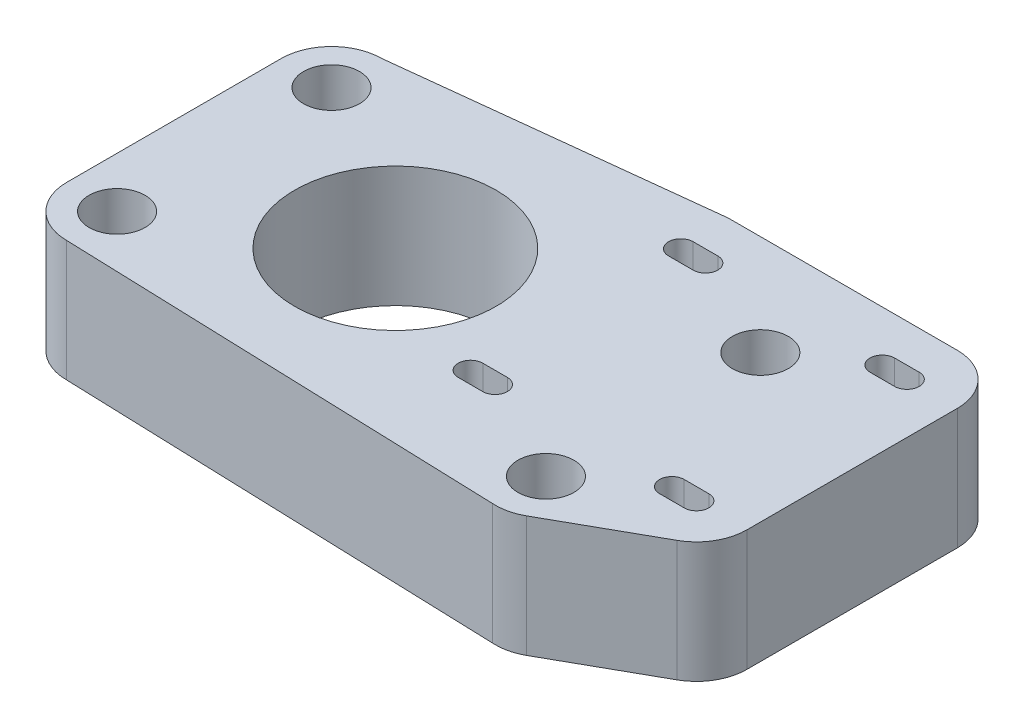
SolidWorks part; units mm, degrees
ref_plane "Front Plane" through (0, 0, 0) normal (0, 0, 1) x (1, 0, 0)
ref_plane "Top Plane" through (0, 0, 0) normal (0, 1, 0) x (1, 0, 0)
ref_plane "Right Plane" through (0, 0, 0) normal (1, 0, 0) x (0, 0, -1)
sketch "Sketch1" plane through (0, 0, 0) normal (0, 1, 0) x (1, 0, 0)
  line L0 (50.75, -48.725) -> (50.75, -55.125) construction
  line L1 (75.25, 55.125) -> (-75.25, 55.125)
  line L2 (75.25, 55.125) -> (75.25, -55.125)
  line L3 (75.25, -55.125) -> (-75.25, -55.125)
  line L4 (-75.25, 55.125) -> (-75.25, -55.125)
  line L5 (75.25, 55.125) -> (-75.25, -55.125) construction
  line L6 (75.25, -55.125) -> (-75.25, 55.125) construction
  line L7 (-48.4, -45.375) -> (-48.4, -55.125) construction
  line L8 (-48.4, -45.375) -> (-48.4, -42.875) construction
  line L9 (-48.4, -42.875) -> (-48.4, -40.375) construction
  line L10 (-48.4, -40.375) -> (-48.4, 2.525) construction
  line L12 (-50.9, -42.875) -> (-75.25, -42.875) construction
  line L13 (53.25, -46.225) -> (75.25, -46.225) construction
  line L14 (50.75, -43.725) -> (50.75, -0.825) construction
  circle A0 centre (-48.4, -42.875) radius 2.5
  circle A1 centre (50.75, -46.225) radius 2.5
  circle A2 centre (-48.4, 5.025) radius 2.5
  circle A3 centre (50.75, 1.675) radius 2.5
  point P0 (0, 0)
  dimension "D3" = 5
  dimension "D1" = 150.5
  dimension "D2" = 110.25
  dimension "D4" = 22
  dimension "D5" = 24.35
  dimension "D6" = 6.4
  dimension "D7" = 9.75
  dimension "D8" = 42.9
extrude "Boss-Extrude1" add sketch "Sketch1" along normal blind 27
sketch "Sketch2" plane through (0, 27, 0) normal (0, 1, 0) x (1, 0, 0)
  line L0 (22.0573, -34.1413) -> (24.5573, -34.1413) construction
  line L2 (22.0573, -29.6413) -> (22.0573, -38.6413) construction
  line L3 (27.0573, -34.1413) -> (24.5573, -34.1413) construction
  line L4 (27.0573, -38.6413) -> (27.0573, -29.6413) construction
  line L6 (67.0573, 12.8587) -> (69.5573, 12.8587) construction
  line L7 (67.0573, 17.3587) -> (67.0573, 8.3587) construction
  line L8 (69.5573, 12.8587) -> (72.0573, 12.8587) construction
  line L9 (72.0573, 8.3587) -> (72.0573, 17.3587) construction
  line L10 (24.5573, -34.1413) -> (69.5573, -34.1413) construction
  line L11 (69.5573, -34.1413) -> (69.5573, 12.8587) construction
  line L12 (69.5573, 12.8587) -> (24.5573, 12.8587) construction
  line L13 (24.5573, 12.8587) -> (24.5573, -34.1413) construction
  circle A3 centre (24.5573, -34.1413) radius 2.75
  circle A4 centre (69.5573, -34.1413) radius 2.75
  circle A5 centre (24.5573, 12.8587) radius 2.75
  circle A6 centre (69.5573, 12.8587) radius 2.75
  dimension "D1" = 5.5
sketch "Sketch3" plane through (0, 0, 0) normal (0, 1, 0) x (1, 0, 0)
  line L1 (-75.25, 55.125) -> (75.25, 55.125)
  line L2 (-75.25, 55.125) -> (-75.25, -55.125)
  line L3 (-75.25, -55.125) -> (75.25, -55.125)
  line L4 (75.25, 55.125) -> (75.25, -55.125)
  line L5 (150, 100) -> (-150, 100)
  line L6 (150, 100) -> (150, -100)
  line L7 (150, -100) -> (-150, -100)
  line L8 (-150, 100) -> (-150, -100)
  line L9 (150, 100) -> (-150, -100) construction
  line L10 (150, -100) -> (-150, 100) construction
  point P6 (0, 0)
  dimension "D1" = 200
  dimension "D2" = 300
extrude "Boss-Extrude2" add sketch "Sketch3" along normal up to surface (27 mm away) up to face at (0, 27, 0)
sketch "Sketch4" plane through (0, 27, 0) normal (0, 1, 0) x (1, 0, 0)
  circle A0 centre (-48.4, 5.025) radius 6.25
  circle A1 centre (-48.4, -42.875) radius 6.25
  circle A2 centre (50.75, -46.225) radius 6.25
  circle A3 centre (50.75, 1.675) radius 6.25
  dimension "D1" = 12.5
extrude "Cut-Extrude2" cut sketch "Sketch4" against normal blind 9
sketch "Sketch5" plane through (0, 27, 0) normal (0, 1, 0) x (1, 0, 0)
  line L0 (21.8073, 15.6087) -> (27.3073, 15.6087)
  line L1 (21.8073, 10.1087) -> (27.3073, 10.1087)
  line L2 (24.5573, -10.6413) -> (69.5573, -10.6413) construction
  line L3 (24.5573, 12.8587) -> (24.5573, -34.1413) construction
  line L4 (69.5573, -34.1413) -> (69.5573, 12.8587) construction
  line L5 (47.0573, 12.8587) -> (47.0573, -34.1413) construction
  line L6 (69.5573, 12.8587) -> (24.5573, 12.8587) construction
  line L7 (24.5573, -34.1413) -> (69.5573, -34.1413) construction
  line L8 (72.3073, 10.1087) -> (66.8073, 10.1087)
  line L9 (72.3073, 15.6087) -> (66.8073, 15.6087)
  line L10 (72.3073, -36.8913) -> (66.8073, -36.8913)
  line L11 (72.3073, -31.3913) -> (66.8073, -31.3913)
  line L12 (21.8073, -31.3913) -> (27.3073, -31.3913)
  line L13 (21.8073, -36.8913) -> (27.3073, -36.8913)
  circle A0 centre (24.5573, 12.8587) radius 2.75
  circle A1 centre (21.8073, 12.8587) radius 2.75
  circle A2 centre (27.3073, 12.8587) radius 2.75
  circle A3 centre (24.5573, 12.8587) radius 2.75 construction
  circle A4 centre (66.8073, 12.8587) radius 2.75
  circle A5 centre (72.3073, 12.8587) radius 2.75
  circle A6 centre (69.5573, 12.8587) radius 2.75
  circle A7 centre (69.5573, -34.1413) radius 2.75
  circle A8 centre (72.3073, -34.1413) radius 2.75
  circle A9 centre (66.8073, -34.1413) radius 2.75
  circle A10 centre (27.3073, -34.1413) radius 2.75
  circle A11 centre (21.8073, -34.1413) radius 2.75
  circle A12 centre (24.5573, -34.1413) radius 2.75
extrude "Cut-Extrude3" cut sketch "Sketch5" against normal through all contours A1 A0 | A2 A0 A1 | A2 A0 | A2 L0 A0 | A1 A0 L0 | A0 A1 | A0 A2 | A2 A1 A0 | A1 L1 A0 | A2 A0 L1 | A6 A4 A5 | A4 A6 L9 | A4 A6 | A6 A4 | L9 A6 A5 | A5 A6 | A6 A5 | L8 A6 A4 | A5 A6 L8 | A6 A5 A4 | A9 A7 | A8 A7 | A7 A8 | A9 A8 A7 | A7 A9 | A9 A7 A8 | A8 L11 A7 | A9 A7 L11 | A8 A7 L10 | A9 L10 A7 | A11 A12 | A12 A11 A10 | A10 A12 | A11 A12 L12 | L12 A12 A10 | A10 A12 L13 | L13 A12 A11 | A12 A10 A11 | A12 A11 | A12 A10
sketch "Sketch6" plane through (0, 0, 0) normal (0, -1, 0) x (1, 0, 0)
  line L0 (21.8073, 40.3913) -> (27.3073, 40.3913)
  line L1 (21.8073, 27.8913) -> (27.3073, 27.8913)
  line L2 (24.5573, 10.6413) -> (69.5573, 10.6413) construction
  line L3 (24.5573, -12.8587) -> (24.5573, 34.1413) construction
  line L4 (69.5573, 34.1413) -> (69.5573, -12.8587) construction
  line L5 (69.5573, 10.6413) -> (47.0573, 34.1413) construction
  line L6 (24.5573, 34.1413) -> (69.5573, 34.1413) construction
  line L7 (47.0573, 34.1413) -> (47.0573, -12.8587) construction
  line L8 (69.5573, -12.8587) -> (24.5573, -12.8587) construction
  line L9 (72.3073, 27.8913) -> (66.8073, 27.8913)
  line L10 (72.3073, 40.3913) -> (66.8073, 40.3913)
  line L11 (72.3073, -19.1087) -> (66.8073, -19.1087)
  line L12 (72.3073, -6.6087) -> (66.8073, -6.6087)
  line L13 (21.8073, -6.6087) -> (27.3073, -6.6087)
  line L14 (21.8073, -19.1087) -> (27.3073, -19.1087)
  circle A0 centre (21.8073, 34.1413) radius 6.25
  circle A1 centre (27.3073, 34.1413) radius 6.25
  circle A3 centre (66.8073, 34.1413) radius 6.25
  circle A4 centre (72.3073, 34.1413) radius 6.25
  circle A5 centre (72.3073, -12.8587) radius 6.25
  circle A6 centre (66.8073, -12.8587) radius 6.25
  circle A7 centre (27.3073, -12.8587) radius 6.25
  circle A8 centre (21.8073, -12.8587) radius 6.25
  arc M3 (27.3073, -10.1087) -> (27.3073, -15.6087) centre (27.3073, -12.8587) cw
  line M4 (27.3073, -15.6087) -> (21.8073, -15.6087)
  arc M5 (21.8073, -15.6087) -> (21.8073, -10.1087) centre (21.8073, -12.8587) cw
  line M6 (21.8073, -10.1087) -> (27.3073, -10.1087)
  line M15 (72.3073, -15.6087) -> (66.8073, -15.6087)
  arc M16 (66.8073, -15.6087) -> (66.8073, -10.1087) centre (66.8073, -12.8587) cw
  line M17 (66.8073, -10.1087) -> (72.3073, -10.1087)
  arc M18 (72.3073, -10.1087) -> (72.3073, -15.6087) centre (72.3073, -12.8587) cw
  arc M19 (66.8073, 31.3913) -> (66.8073, 36.8913) centre (66.8073, 34.1413) cw
  line M20 (66.8073, 36.8913) -> (72.3073, 36.8913)
  arc M21 (72.3073, 36.8913) -> (72.3073, 31.3913) centre (72.3073, 34.1413) cw
  line M22 (72.3073, 31.3913) -> (66.8073, 31.3913)
  line M23 (27.3073, 31.3913) -> (21.8073, 31.3913)
  arc M24 (21.8073, 31.3913) -> (21.8073, 36.8913) centre (21.8073, 34.1413) cw
  line M25 (21.8073, 36.8913) -> (27.3073, 36.8913)
  arc M26 (27.3073, 36.8913) -> (27.3073, 31.3913) centre (27.3073, 34.1413) cw
  dimension "D1" = 12.5
extrude "Cut-Extrude4" cut sketch "Sketch6" against normal blind 9 contours A1 A0 M24 | A1 L0 A0 | A1 A0 M26 | A0 A1 M24 M25 M26 | A1 A0 M24 M26 M23 | A1 A0 L1 | A3 A4 L10 | A4 A3 M21 | A4 A3 M19 M20 M21 | A3 A4 M19 | A4 A3 M21 M22 M19 | L9 A4 A3 | A6 A5 M16 | A6 A5 L12 | A6 A5 M18 | A6 A5 M18 M16 M17 | A6 L11 A5 | A5 A6 M18 M15 M16 | A8 A7 M5 | L13 A8 A7 | A7 A8 M3 | A8 A7 M5 M6 M3 | A8 A7 M3 M4 M5 | A7 A8 L14
sketch "Sketch7" plane through (0, 0, 0) normal (0, 1, 0) x (1, 0, 0)
  line L0 (-59.65, 5.025) -> (-59.65, -42.875)
  line L5 (-48.4, -54.125) -> (50.75, -57.475)
  line L6 (56.2508, -56.0384) -> (77.8081, -43.9547)
  line L7 (83.5573, -34.1413) -> (83.5573, 12.8587)
  line L8 (72.3073, 24.1087) -> (21.8073, 24.1087)
  line L9 (20.5486, 24.0381) -> (-48.4, 16.275)
  line L11 (-150, 100) -> (150, 100)
  line L12 (-150, 100) -> (-150, -100)
  line L13 (-150, -100) -> (150, -100)
  line L14 (150, 100) -> (150, -100)
  circle A0 centre (-48.4, -42.875) radius 11.25
  circle A1 centre (-48.4, 5.025) radius 11.25
  circle A2 centre (72.3073, 12.8587) radius 11.25
  circle A3 centre (72.3073, -34.1413) radius 11.25
  circle A4 centre (50.75, -46.225) radius 11.25
  circle A5 centre (21.8073, 12.8587) radius 11.25
  circle A6 centre (-48.4, 5.025) radius 6.25 construction
  circle A7 centre (-10.187, -18.925) radius 33.8481 construction
  circle A8 centre (-10.187, -18.925) radius 22.5
  dimension "D1" = 5
  dimension "D2" = 45
extrude "Cut-Extrude5" cut sketch "Sketch7" along normal through all contours L14 L11 L12 L13 A5 L8 A2 L7 A3 L6 A4 L5 A0 L0 A1 L9 | A8
